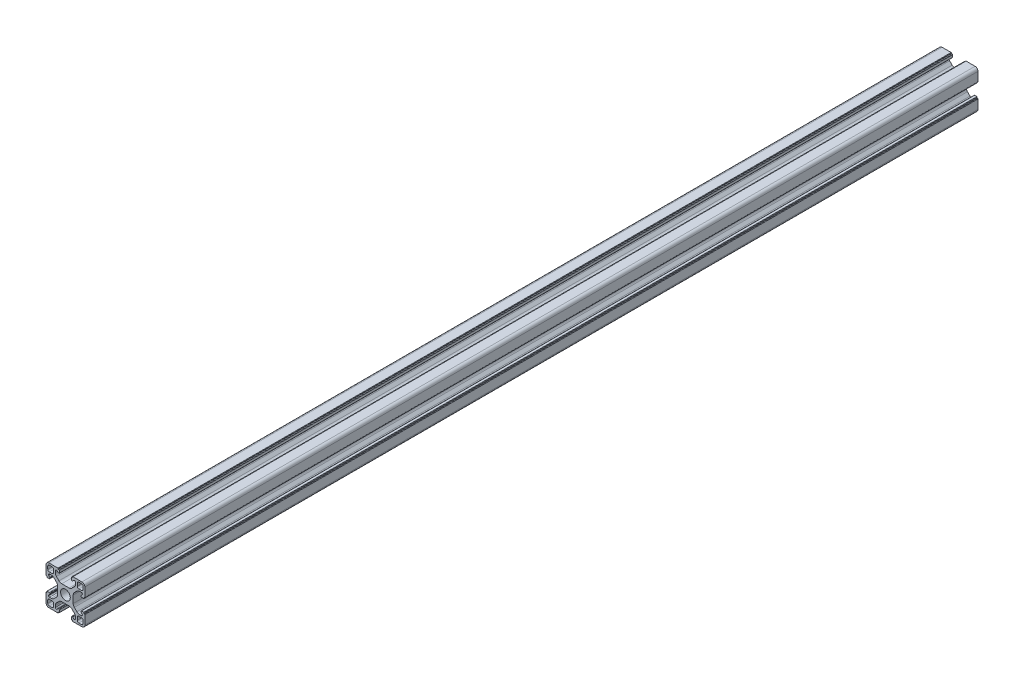
SolidWorks part; units mm, degrees
material "1060 Сплав"
ref_plane "Спереди" through (0, 0, 0) normal (0, 0, 1) x (1, 0, 0)
ref_plane "Сверху" through (0, 0, 0) normal (0, 1, 0) x (1, 0, 0)
ref_plane "Справа" through (0, 0, 0) normal (1, 0, 0) x (0, 0, -1)
sketch "Эскиз1" plane through (0, 0, 0) normal (0, 0, 1) x (1, 0, 0)
  line L0 (-22.0052, 70.3096) -> (-25.0052, 67.3096) construction
  line L1 (-31.1052, 65.2096) -> (-29.2064, 65.2096)
  line L2 (-31.1052, 61.2096) -> (-21.1052, 71.2096) construction
  line L3 (-23.5052, 68.8096) -> (-25.0052, 70.3096) construction
  line L4 (-27.7922, 65.7954) -> (-26.4909, 67.0967)
  line L5 (-24.2052, 67.3096) -> (-22.8052, 67.3096)
  line L6 (-25.0052, 68.1096) -> (-25.0052, 69.5096)
  line L7 (-22.8052, 70.3096) -> (-24.2052, 70.3096)
  line L8 (-25.9052, 69.4096) -> (-25.9052, 68.5109)
  line L9 (-27.3419, 69.2829) -> (-26.8616, 69.7632)
  line L10 (-27.9052, 70.7587) -> (-27.4052, 70.7587)
  line L11 (-27.5187, 69.2096) -> (-27.8052, 69.2096)
  line L12 (-26.508, 69.9096) -> (-26.4052, 69.9096)
  line L13 (-27.4052, 71.0596) -> (-27.4052, 70.7587)
  line L14 (-28.0552, 70.6087) -> (-28.0552, 69.4596)
  line L15 (-22.6052, 71.2096) -> (-27.2552, 71.2096)
  line L16 (-22.0052, 69.5096) -> (-22.0052, 68.1096)
  line L17 (-21.1052, 69.7096) -> (-21.1052, 65.0596)
  line L18 (-21.7061, 64.2596) -> (-22.8552, 64.2596)
  line L19 (-21.2552, 64.9096) -> (-21.5561, 64.9096)
  line L20 (-22.4052, 65.8068) -> (-22.4052, 65.9096)
  line L21 (-23.1052, 64.7961) -> (-23.1052, 64.5096)
  line L22 (-21.5561, 64.4096) -> (-21.5561, 64.9096)
  line L23 (-23.0319, 64.9729) -> (-22.5516, 65.4532)
  line L24 (-22.9052, 66.4096) -> (-23.8039, 66.4096)
  line L25 (-26.5194, 64.5226) -> (-25.2181, 65.8239)
  line L26 (-27.1052, 61.2096) -> (-27.1052, 63.1084)
  line L27 (-27.1052, 61.2096) -> (-27.1052, 59.3109)
  line L28 (-26.5194, 57.8967) -> (-25.2181, 56.5954)
  line L29 (-25.0052, 54.3096) -> (-25.0052, 52.9096)
  line L30 (-24.2052, 55.1096) -> (-22.8052, 55.1096)
  line L31 (-22.0052, 52.9096) -> (-22.0052, 54.3096)
  line L32 (-22.9052, 56.0096) -> (-23.8039, 56.0096)
  line L33 (-23.0319, 57.4464) -> (-22.5516, 56.9661)
  line L34 (-21.5561, 58.0096) -> (-21.5561, 57.5096)
  line L35 (-23.1052, 57.6232) -> (-23.1052, 57.9096)
  line L36 (-22.4052, 56.6125) -> (-22.4052, 56.5096)
  line L37 (-21.2552, 57.5096) -> (-21.5561, 57.5096)
  line L38 (-21.7061, 58.1596) -> (-22.8552, 58.1596)
  line L39 (-21.1052, 52.7096) -> (-21.1052, 57.3596)
  line L40 (-22.8052, 52.1096) -> (-24.2052, 52.1096)
  line L41 (-22.6052, 51.2096) -> (-27.2552, 51.2096)
  line L42 (-28.0552, 51.8106) -> (-28.0552, 52.9596)
  line L43 (-27.4052, 51.3596) -> (-27.4052, 51.6606)
  line L44 (-26.508, 52.5096) -> (-26.4052, 52.5096)
  line L45 (-27.5187, 53.2096) -> (-27.8052, 53.2096)
  line L46 (-27.9052, 51.6606) -> (-27.4052, 51.6606)
  line L47 (-27.3419, 53.1364) -> (-26.8616, 52.6561)
  line L48 (-25.9052, 53.0096) -> (-25.9052, 53.9084)
  line L49 (-27.7922, 56.6239) -> (-26.4909, 55.3226)
  line L50 (-31.1052, 57.2096) -> (-29.2064, 57.2096)
  line L51 (-22.0052, 52.1096) -> (-25.0052, 55.1096) construction
  line L52 (-31.1052, 61.2096) -> (-21.1052, 51.2096) construction
  line L53 (-23.5052, 53.6096) -> (-22.0052, 55.1096) construction
  line L54 (-31.1052, 57.2096) -> (-33.0039, 57.2096)
  line L55 (-34.4181, 56.6239) -> (-35.7194, 55.3226)
  line L56 (-38.0052, 55.1096) -> (-39.4052, 55.1096)
  line L57 (-37.2052, 54.3096) -> (-37.2052, 52.9096)
  line L58 (-39.4052, 52.1096) -> (-38.0052, 52.1096)
  line L59 (-36.3052, 53.0096) -> (-36.3052, 53.9084)
  line L60 (-34.8684, 53.1364) -> (-35.3487, 52.6561)
  line L61 (-34.3052, 51.6606) -> (-34.8052, 51.6606)
  line L62 (-34.6916, 53.2096) -> (-34.4052, 53.2096)
  line L63 (-35.7023, 52.5096) -> (-35.8052, 52.5096)
  line L64 (-34.8052, 51.3596) -> (-34.8052, 51.6606)
  line L65 (-34.1552, 51.8106) -> (-34.1552, 52.9596)
  line L66 (-39.6052, 51.2096) -> (-34.9552, 51.2096)
  line L67 (-40.2052, 52.9096) -> (-40.2052, 54.3096)
  line L68 (-41.1052, 52.7096) -> (-41.1052, 57.3596)
  line L69 (-40.5042, 58.1596) -> (-39.3552, 58.1596)
  line L70 (-40.9552, 57.5096) -> (-40.6542, 57.5096)
  line L71 (-39.8052, 56.6125) -> (-39.8052, 56.5096)
  line L72 (-39.1052, 57.6232) -> (-39.1052, 57.9096)
  line L73 (-40.6542, 58.0096) -> (-40.6542, 57.5096)
  line L74 (-39.1784, 57.4464) -> (-39.6587, 56.9661)
  line L75 (-39.3052, 56.0096) -> (-38.4064, 56.0096)
  line L76 (-35.6909, 57.8967) -> (-36.9922, 56.5954)
  line L77 (-35.1052, 61.2096) -> (-35.1052, 59.3109)
  line L78 (-40.2052, 52.1096) -> (-37.2052, 55.1096) construction
  line L79 (-31.1052, 61.2096) -> (-41.1052, 51.2096) construction
  line L80 (-38.7052, 53.6096) -> (-37.2052, 52.1096) construction
  line L81 (-35.1052, 61.2096) -> (-35.1052, 63.1084)
  line L82 (-35.6909, 64.5226) -> (-36.9922, 65.8239)
  line L83 (-37.2052, 68.1096) -> (-37.2052, 69.5096)
  line L84 (-38.0052, 67.3096) -> (-39.4052, 67.3096)
  line L85 (-40.2052, 69.5096) -> (-40.2052, 68.1096)
  line L86 (-39.3052, 66.4096) -> (-38.4064, 66.4096)
  line L87 (-39.1784, 64.9729) -> (-39.6587, 65.4532)
  line L88 (-40.6542, 64.4096) -> (-40.6542, 64.9096)
  line L89 (-39.1052, 64.7961) -> (-39.1052, 64.5096)
  line L90 (-39.8052, 65.8068) -> (-39.8052, 65.9096)
  line L91 (-40.9552, 64.9096) -> (-40.6542, 64.9096)
  line L92 (-40.5042, 64.2596) -> (-39.3552, 64.2596)
  line L93 (-41.1052, 69.7096) -> (-41.1052, 65.0596)
  line L94 (-39.4052, 70.3096) -> (-38.0052, 70.3096)
  line L95 (-39.6052, 71.2096) -> (-34.9552, 71.2096)
  line L96 (-34.1552, 70.6087) -> (-34.1552, 69.4596)
  line L97 (-34.8052, 71.0596) -> (-34.8052, 70.7587)
  line L98 (-35.7023, 69.9096) -> (-35.8052, 69.9096)
  line L99 (-34.6916, 69.2096) -> (-34.4052, 69.2096)
  line L100 (-34.3052, 70.7587) -> (-34.8052, 70.7587)
  line L101 (-34.8684, 69.2829) -> (-35.3487, 69.7632)
  line L102 (-36.3052, 69.4096) -> (-36.3052, 68.5109)
  line L103 (-34.4181, 65.7954) -> (-35.7194, 67.0967)
  line L104 (-31.1052, 65.2096) -> (-33.0039, 65.2096)
  line L105 (-42.8692, 61.2096) -> (-19.6008, 61.2096) construction
  line L106 (-40.2052, 70.3096) -> (-37.2052, 67.3096) construction
  line L107 (-31.1052, 49.1232) -> (-31.1052, 71.9286) construction
  line L108 (-31.1052, 61.2096) -> (-41.1052, 71.2096) construction
  line L109 (-38.7052, 68.8096) -> (-40.2052, 67.3096) construction
  arc A0 (-22.0052, 69.5096) -> (-22.8052, 70.3096) centre (-22.8052, 69.5096) ccw
  arc A1 (-24.2052, 70.3096) -> (-25.0052, 69.5096) centre (-24.2052, 69.5096) ccw
  arc A2 (-24.2052, 67.3096) -> (-25.0052, 68.1096) centre (-24.2052, 68.1096) cw
  arc A3 (-22.6052, 71.2096) -> (-21.1052, 69.7096) centre (-22.6052, 69.7096) cw
  arc A4 (-27.9052, 70.7587) -> (-28.0552, 70.6087) centre (-27.9052, 70.6087) ccw
  arc A5 (-27.2552, 71.2096) -> (-27.4052, 71.0596) centre (-27.2552, 71.0596) ccw
  arc A6 (-27.5187, 69.2096) -> (-27.3419, 69.2829) centre (-27.5187, 69.4596) ccw
  arc A7 (-27.8052, 69.2096) -> (-28.0552, 69.4596) centre (-27.8052, 69.4596) cw
  arc A8 (-26.8616, 69.7632) -> (-26.508, 69.9096) centre (-26.508, 69.4096) cw
  arc A9 (-26.4052, 69.9096) -> (-25.9052, 69.4096) centre (-26.4052, 69.4096) cw
  arc A10 (-28.6052, 61.2096) -> (-31.1052, 63.7096) centre (-31.1052, 61.2096) ccw
  arc A11 (-29.2064, 65.2096) -> (-27.7922, 65.7954) centre (-29.2064, 67.2096) ccw
  arc A12 (-25.9052, 68.5109) -> (-26.4909, 67.0967) centre (-27.9052, 68.5109) cw
  arc A13 (-22.0052, 68.1096) -> (-22.8052, 67.3096) centre (-22.8052, 68.1096) cw
  arc A14 (-22.4052, 65.9096) -> (-22.9052, 66.4096) centre (-22.9052, 65.9096) ccw
  arc A15 (-22.5516, 65.4532) -> (-22.4052, 65.8068) centre (-22.9052, 65.8068) ccw
  arc A16 (-23.1052, 64.5096) -> (-22.8552, 64.2596) centre (-22.8552, 64.5096) ccw
  arc A17 (-23.1052, 64.7961) -> (-23.0319, 64.9729) centre (-22.8552, 64.7961) cw
  arc A18 (-21.1052, 65.0596) -> (-21.2552, 64.9096) centre (-21.2552, 65.0596) cw
  arc A19 (-21.5561, 64.4096) -> (-21.7061, 64.2596) centre (-21.7061, 64.4096) cw
  arc A20 (-23.8039, 66.4096) -> (-25.2181, 65.8239) centre (-23.8039, 64.4096) ccw
  arc A21 (-27.1052, 63.1084) -> (-26.5194, 64.5226) centre (-25.1052, 63.1084) cw
  arc A22 (-22.8052, 52.1096) -> (-22.0052, 52.9096) centre (-22.8052, 52.9096) ccw
  arc A23 (-22.0052, 54.3096) -> (-22.8052, 55.1096) centre (-22.8052, 54.3096) ccw
  arc A24 (-25.0052, 54.3096) -> (-24.2052, 55.1096) centre (-24.2052, 54.3096) cw
  arc A25 (-21.1052, 52.7096) -> (-22.6052, 51.2096) centre (-22.6052, 52.7096) cw
  arc A26 (-21.5561, 58.0096) -> (-21.7061, 58.1596) centre (-21.7061, 58.0096) ccw
  arc A27 (-21.1052, 57.3596) -> (-21.2552, 57.5096) centre (-21.2552, 57.3596) ccw
  arc A28 (-23.1052, 57.6232) -> (-23.0319, 57.4464) centre (-22.8552, 57.6232) ccw
  arc A29 (-23.1052, 57.9096) -> (-22.8552, 58.1596) centre (-22.8552, 57.9096) cw
  arc A30 (-22.5516, 56.9661) -> (-22.4052, 56.6125) centre (-22.9052, 56.6125) cw
  arc A31 (-22.4052, 56.5096) -> (-22.9052, 56.0096) centre (-22.9052, 56.5096) cw
  arc A32 (-31.1052, 58.7096) -> (-28.6052, 61.2096) centre (-31.1052, 61.2096) ccw
  arc A33 (-27.1052, 59.3109) -> (-26.5194, 57.8967) centre (-25.1052, 59.3109) ccw
  arc A34 (-23.8039, 56.0096) -> (-25.2181, 56.5954) centre (-23.8039, 58.0096) cw
  arc A35 (-24.2052, 52.1096) -> (-25.0052, 52.9096) centre (-24.2052, 52.9096) cw
  arc A36 (-26.4052, 52.5096) -> (-25.9052, 53.0096) centre (-26.4052, 53.0096) ccw
  arc A37 (-26.8616, 52.6561) -> (-26.508, 52.5096) centre (-26.508, 53.0096) ccw
  arc A38 (-27.8052, 53.2096) -> (-28.0552, 52.9596) centre (-27.8052, 52.9596) ccw
  arc A39 (-27.5187, 53.2096) -> (-27.3419, 53.1364) centre (-27.5187, 52.9596) cw
  arc A40 (-27.2552, 51.2096) -> (-27.4052, 51.3596) centre (-27.2552, 51.3596) cw
  arc A41 (-27.9052, 51.6606) -> (-28.0552, 51.8106) centre (-27.9052, 51.8106) cw
  arc A42 (-25.9052, 53.9084) -> (-26.4909, 55.3226) centre (-27.9052, 53.9084) ccw
  arc A43 (-29.2064, 57.2096) -> (-27.7922, 56.6239) centre (-29.2064, 55.2096) cw
  arc A44 (-40.2052, 52.9096) -> (-39.4052, 52.1096) centre (-39.4052, 52.9096) ccw
  arc A45 (-38.0052, 52.1096) -> (-37.2052, 52.9096) centre (-38.0052, 52.9096) ccw
  arc A46 (-38.0052, 55.1096) -> (-37.2052, 54.3096) centre (-38.0052, 54.3096) cw
  arc A47 (-39.6052, 51.2096) -> (-41.1052, 52.7096) centre (-39.6052, 52.7096) cw
  arc A48 (-34.3052, 51.6606) -> (-34.1552, 51.8106) centre (-34.3052, 51.8106) ccw
  arc A49 (-34.9552, 51.2096) -> (-34.8052, 51.3596) centre (-34.9552, 51.3596) ccw
  arc A50 (-34.6916, 53.2096) -> (-34.8684, 53.1364) centre (-34.6916, 52.9596) ccw
  arc A51 (-34.4052, 53.2096) -> (-34.1552, 52.9596) centre (-34.4052, 52.9596) cw
  arc A52 (-35.3487, 52.6561) -> (-35.7023, 52.5096) centre (-35.7023, 53.0096) cw
  arc A53 (-35.8052, 52.5096) -> (-36.3052, 53.0096) centre (-35.8052, 53.0096) cw
  arc A54 (-33.6052, 61.2096) -> (-31.1052, 58.7096) centre (-31.1052, 61.2096) ccw
  arc A55 (-33.0039, 57.2096) -> (-34.4181, 56.6239) centre (-33.0039, 55.2096) ccw
  arc A56 (-36.3052, 53.9084) -> (-35.7194, 55.3226) centre (-34.3052, 53.9084) cw
  arc A57 (-40.2052, 54.3096) -> (-39.4052, 55.1096) centre (-39.4052, 54.3096) cw
  arc A58 (-39.8052, 56.5096) -> (-39.3052, 56.0096) centre (-39.3052, 56.5096) ccw
  arc A59 (-39.6587, 56.9661) -> (-39.8052, 56.6125) centre (-39.3052, 56.6125) ccw
  arc A60 (-39.1052, 57.9096) -> (-39.3552, 58.1596) centre (-39.3552, 57.9096) ccw
  arc A61 (-39.1052, 57.6232) -> (-39.1784, 57.4464) centre (-39.3552, 57.6232) cw
  arc A62 (-41.1052, 57.3596) -> (-40.9552, 57.5096) centre (-40.9552, 57.3596) cw
  arc A63 (-40.6542, 58.0096) -> (-40.5042, 58.1596) centre (-40.5042, 58.0096) cw
  arc A64 (-38.4064, 56.0096) -> (-36.9922, 56.5954) centre (-38.4064, 58.0096) ccw
  arc A65 (-35.1052, 59.3109) -> (-35.6909, 57.8967) centre (-37.1052, 59.3109) cw
  arc A66 (-39.4052, 70.3096) -> (-40.2052, 69.5096) centre (-39.4052, 69.5096) ccw
  arc A67 (-40.2052, 68.1096) -> (-39.4052, 67.3096) centre (-39.4052, 68.1096) ccw
  arc A68 (-37.2052, 68.1096) -> (-38.0052, 67.3096) centre (-38.0052, 68.1096) cw
  arc A69 (-41.1052, 69.7096) -> (-39.6052, 71.2096) centre (-39.6052, 69.7096) cw
  arc A70 (-40.6542, 64.4096) -> (-40.5042, 64.2596) centre (-40.5042, 64.4096) ccw
  arc A71 (-41.1052, 65.0596) -> (-40.9552, 64.9096) centre (-40.9552, 65.0596) ccw
  arc A72 (-39.1052, 64.7961) -> (-39.1784, 64.9729) centre (-39.3552, 64.7961) ccw
  arc A73 (-39.1052, 64.5096) -> (-39.3552, 64.2596) centre (-39.3552, 64.5096) cw
  arc A74 (-39.6587, 65.4532) -> (-39.8052, 65.8068) centre (-39.3052, 65.8068) cw
  arc A75 (-39.8052, 65.9096) -> (-39.3052, 66.4096) centre (-39.3052, 65.9096) cw
  arc A76 (-31.1052, 63.7096) -> (-33.6052, 61.2096) centre (-31.1052, 61.2096) ccw
  arc A77 (-35.1052, 63.1084) -> (-35.6909, 64.5226) centre (-37.1052, 63.1084) ccw
  arc A78 (-38.4064, 66.4096) -> (-36.9922, 65.8239) centre (-38.4064, 64.4096) cw
  arc A79 (-38.0052, 70.3096) -> (-37.2052, 69.5096) centre (-38.0052, 69.5096) cw
  arc A80 (-35.8052, 69.9096) -> (-36.3052, 69.4096) centre (-35.8052, 69.4096) ccw
  arc A81 (-35.3487, 69.7632) -> (-35.7023, 69.9096) centre (-35.7023, 69.4096) ccw
  arc A82 (-34.4052, 69.2096) -> (-34.1552, 69.4596) centre (-34.4052, 69.4596) ccw
  arc A83 (-34.6916, 69.2096) -> (-34.8684, 69.2829) centre (-34.6916, 69.4596) cw
  arc A84 (-34.9552, 71.2096) -> (-34.8052, 71.0596) centre (-34.9552, 71.0596) cw
  arc A85 (-34.3052, 70.7587) -> (-34.1552, 70.6087) centre (-34.3052, 70.6087) cw
  arc A86 (-36.3052, 68.5109) -> (-35.7194, 67.0967) centre (-34.3052, 68.5109) ccw
  arc A87 (-33.0039, 65.2096) -> (-34.4181, 65.7954) centre (-33.0039, 67.2096) cw
  point P0 (-31.1052, 61.2096)
  point P9 (-31.1052, 61.2096)
  point P40 (-22.4052, 64.9096)
  point P93 (-27.4052, 52.5096)
  point P144 (-27.4052, 69.9096)
  point P152 (-22.4052, 57.5096)
  point P153 (-31.1052, 57.2854)
  point P154 (-31.1052, 61.2096)
  point P189 (-39.8052, 57.5096)
  point P228 (-34.8052, 52.5096)
  point P229 (-35.0294, 61.2096)
  point P230 (-31.1052, 61.2096)
  point P268 (-34.8052, 69.9096)
  point P273 (-27.1809, 61.2096)
  point P306 (-39.8052, 64.9096)
  point P307 (-31.1052, 65.1339)
  point P309 (-31.1052, 61.2096)
  dimension "D3" = 5
  dimension "D6" = 2
  dimension "D1" = 2
  dimension "D2" = 6
  dimension "D4" = 4
  dimension "D5" = 0.9
extrude "Бобышка-Вытянуть1" add sketch "Эскиз1" along normal blind 460
